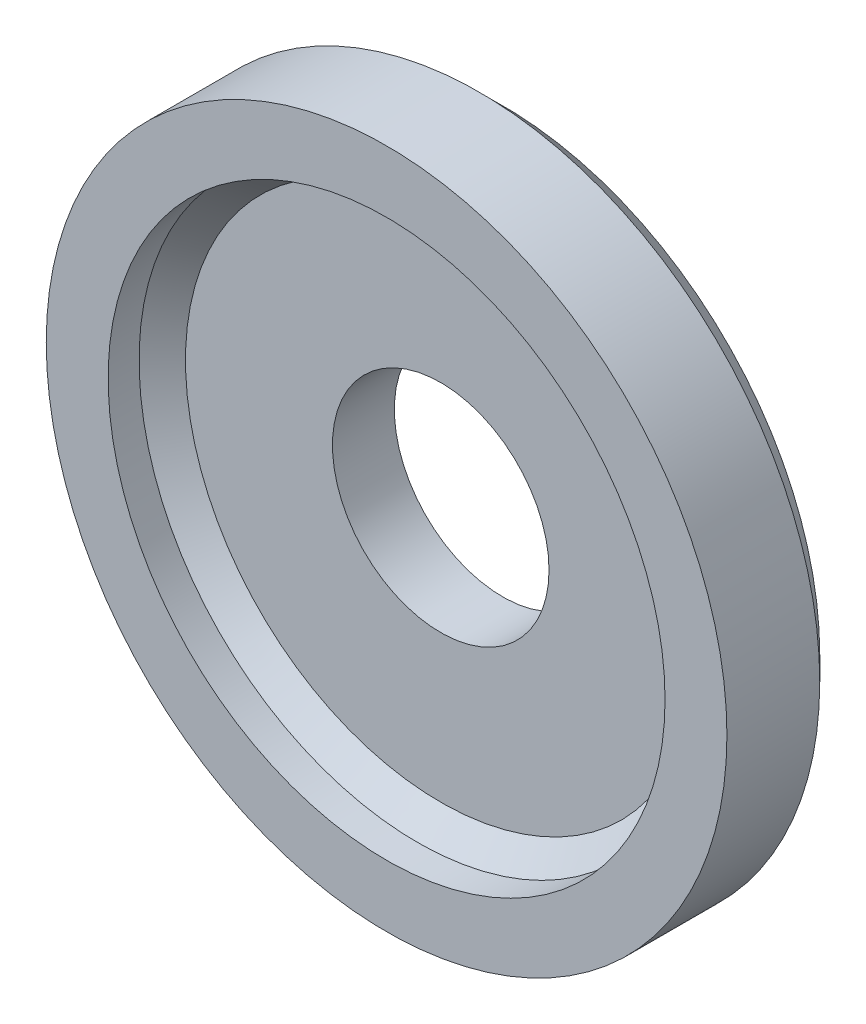
SolidWorks part; units mm, degrees
material "Zinc AC41A Alloy, As Cast"
ref_plane "Plan de face" through (0, 0, 0) normal (0, 0, 1) x (1, 0, 0)
ref_plane "Plan de dessus" through (0, 0, 0) normal (0, 1, 0) x (1, 0, 0)
ref_plane "Plan de droite" through (0, 0, 0) normal (1, 0, 0) x (0, 0, -1)
sketch "Sketch1" plane through (0, 0, 0) normal (0, 0, 1) x (1, 0, 0)
  circle A0 centre (0, 0) radius 11
  circle A1 centre (0, 0) radius 3.5
  dimension "D1" = 22
  dimension "D2" = 7
extrude "Boss-Extrude1" add sketch "Sketch1" along normal blind 3.75
chamfer "Chamfer1" distance 0.75 angle 45 1 edges at (11, 0, 0)
sketch "Sketch2" plane through (0, 0, 3.75) normal (0, 0, 1) x (1, 0, 0)
  circle A0 centre (0, 0) radius 9
  dimension "D1" = 18
extrude "Cut-Extrude1" cut sketch "Sketch2" against normal blind 1.75
chamfer "Chamfer2" distance 0.75 angle 45 1 edges at (9, 0, 2)
